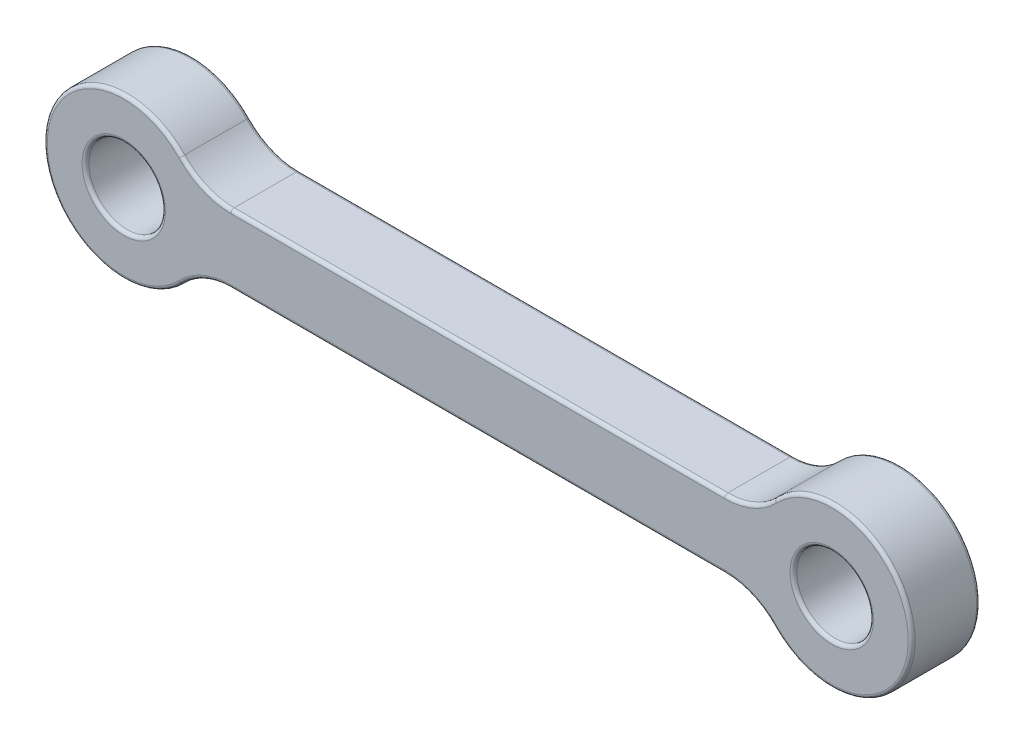
SolidWorks part; units mm, degrees
ref_plane "Front Plane" through (0, 0, 0) normal (0, 0, 1) x (1, 0, 0)
ref_plane "Top Plane" through (0, 0, 0) normal (0, 1, 0) x (1, 0, 0)
ref_plane "Right Plane" through (0, 0, 0) normal (1, 0, 0) x (0, 0, -1)
sketch "Sketch1" plane through (0, 0, 0) normal (0, 0, 1) x (1, 0, 0)
  line L0 (0, 0) -> (31, 0) construction
  line L1 (0, 3.5) -> (31, 3.5) construction
  line L2 (0, -3.5) -> (31, -3.5) construction
  line L3 (15.5, 0) -> (15.5, -3.5) construction
  line L5 (27.8377, -1.5) -> (3.1623, -1.5)
  line L6 (27.8377, -1.5) -> (27.8377, 1.5) construction
  line L7 (27.8377, 1.5) -> (3.1623, 1.5)
  line L8 (3.1623, -1.5) -> (3.1623, 1.5) construction
  line L9 (27.8377, -1.5) -> (3.1623, 1.5) construction
  line L10 (27.8377, 1.5) -> (3.1623, -1.5) construction
  arc A0 (0, 3.5) -> (0, -3.5) centre (0, 0) ccw construction
  arc A1 (31, -3.5) -> (31, 3.5) centre (31, 0) ccw construction
  circle A2 centre (0, 0) radius 1.675
  circle A3 centre (0, 0) radius 3.5
  circle A4 centre (31, 0) radius 1.675
  circle A5 centre (31, 0) radius 3.5
  point P3 (15.5, 0)
  dimension "D3" = 3.35
  dimension "D1" = 31
  dimension "D2" = 7
  dimension "D4" = 3
extrude "Boss-Extrude1" add sketch "Sketch1" along normal mid plane 3 contours A3 A2 | L5 A5 L7 A3 | A5 A4
fillet "Fillet1" radius 3 4 edges at (3.1623, 1.5, 0) (27.8377, 1.5, 0) (3.1623, -1.5, 0) (27.8377, -1.5, 0)
fillet "Fillet2" radius 0.15 20 edges at (32.675, 0, 1.5) (32.675, 0, -1.5) (1.675, 0, 1.5) (1.675, 0, -1.5) (3.5137, 1.7404, 1.5) (3.5137, 1.7404, -1.5) (-3.5, 0, 1.5) (-3.5, 0, -1.5) (3.5137, -1.7404, 1.5) (3.5137, -1.7404, -1.5) (15.5, -1.5, 1.5) (15.5, -1.5, -1.5) (27.4863, -1.7404, 1.5) (27.4863, -1.7404, -1.5) (34.5, 0, -1.5) (34.5, 0, 1.5) (27.4863, 1.7404, 1.5) (27.4863, 1.7404, -1.5) (15.5, 1.5, -1.5) (15.5, 1.5, 1.5)
